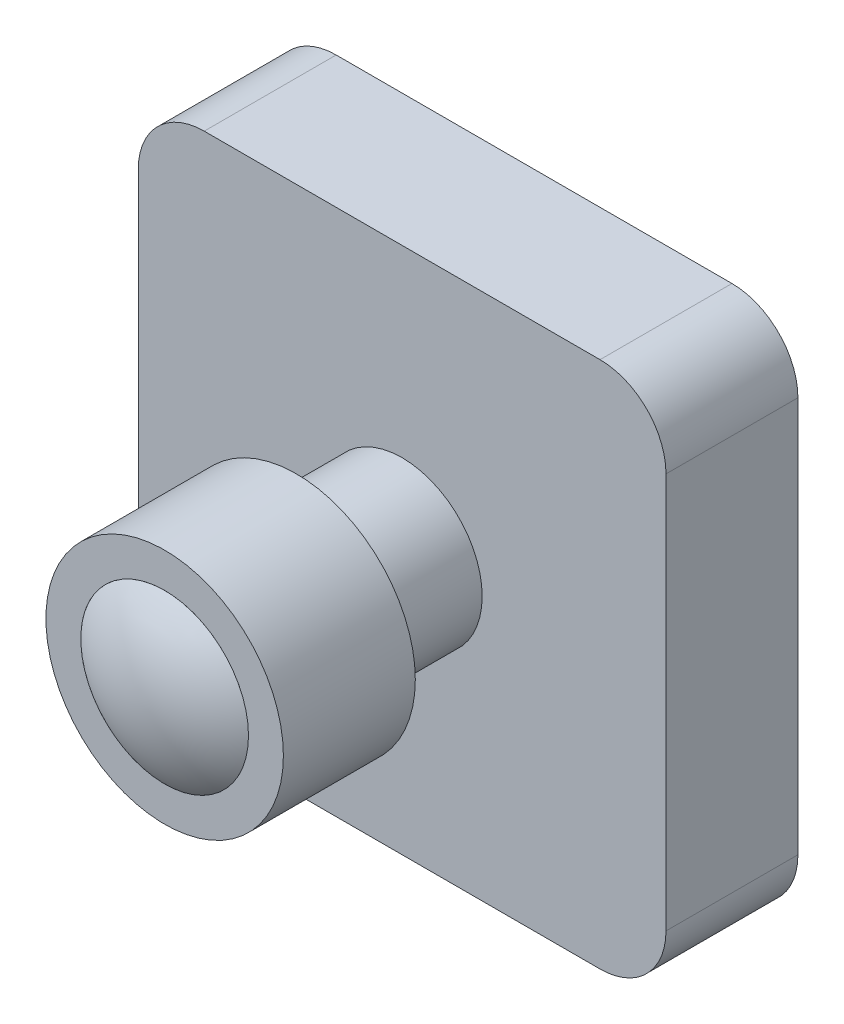
SolidWorks part; units mm, degrees
ref_plane "Спереди" through (0, 0, 0) normal (0, 0, 1) x (1, 0, 0)
ref_plane "Сверху" through (0, 0, 0) normal (0, 1, 0) x (1, 0, 0)
ref_plane "Справа" through (0, 0, 0) normal (1, 0, 0) x (0, 0, -1)
sketch "Эскиз1" plane through (0, 0, 0) normal (0, 0, 1) x (1, 0, 0)
  circle A0 centre (0, 0) radius 9
extrude "Бобышка-Вытянуть1" add sketch "Эскиз1" along normal blind 10
sketch "Эскиз2" plane through (0, 0, 0) normal (0, 1, 0) x (1, 0, 0)
  line L0 (9, -10) -> (0, -10) construction
  line L1 (9, -10) -> (6.355, -10)
  line L2 (6.355, -10) -> (3.422, -2.6876)
  line L3 (3.422, -2.6876) -> (0, -2.6876)
  line L4 (0, -2.6876) -> (0, -11.1189)
  line L5 (0, -11.1189) -> (6.355, -10)
revolve "Вырез-Повернуть1" cut sketch "Эскиз2" angle 360 about L4
sketch "Эскиз3" plane through (0, 0, 2.6876) normal (0, 0, 1) x (1, 0, 0)
  circle A0 centre (0, 0) radius 4.0613
  circle A1 centre (0, 0) radius 2.0344
extrude "Бобышка-Вытянуть2" add sketch "Эскиз3" along normal blind 2
sketch "Эскиз4" plane through (0, 0, 0) normal (0, 0, -1) x (-1, 0, 0)
  circle A0 centre (0, 0) radius 6.0669
extrude "Бобышка-Вытянуть3" add sketch "Эскиз4" along normal blind 8
sketch "Эскиз5" plane through (0, 0, -8) normal (0, 0, -1) x (-1, 0, 0)
  line L1 (-15, -20) -> (15, -20)
  line L2 (-20, -15) -> (-20, 15)
  line L3 (-15, 20) -> (15, 20)
  line L4 (20, -15) -> (20, 15)
  line L5 (-20, -20) -> (20, 20) construction
  line L6 (-20, 20) -> (20, -20) construction
  arc A0 (20, -15) -> (15, -20) centre (15, -15) cw
  arc A1 (-15, -20) -> (-20, -15) centre (-15, -15) cw
  arc A2 (-20, 15) -> (-15, 20) centre (-15, 15) cw
  arc A3 (15, 20) -> (20, 15) centre (15, 15) cw
  point P0 (0, 0)
  dimension "D1" = 5
extrude "Бобышка-Вытянуть4" add sketch "Эскиз5" along normal blind 10 separate body
sketch "Эскиз6" plane through (0, 0, 0) normal (0, 1, 0) x (1, 0, 0)
  line L0 (0, 0) -> (0, -12.0792) construction
  line L1 (0, -12.0792) -> (-2.6859, -12.0792) construction
  arc A0 (0, -12.0792) -> (6.355, -10) centre (0, -1.3278) ccw
surface "Поверхность-Повернуть1" sketch "Эскиз6" parameters "D1"=360
